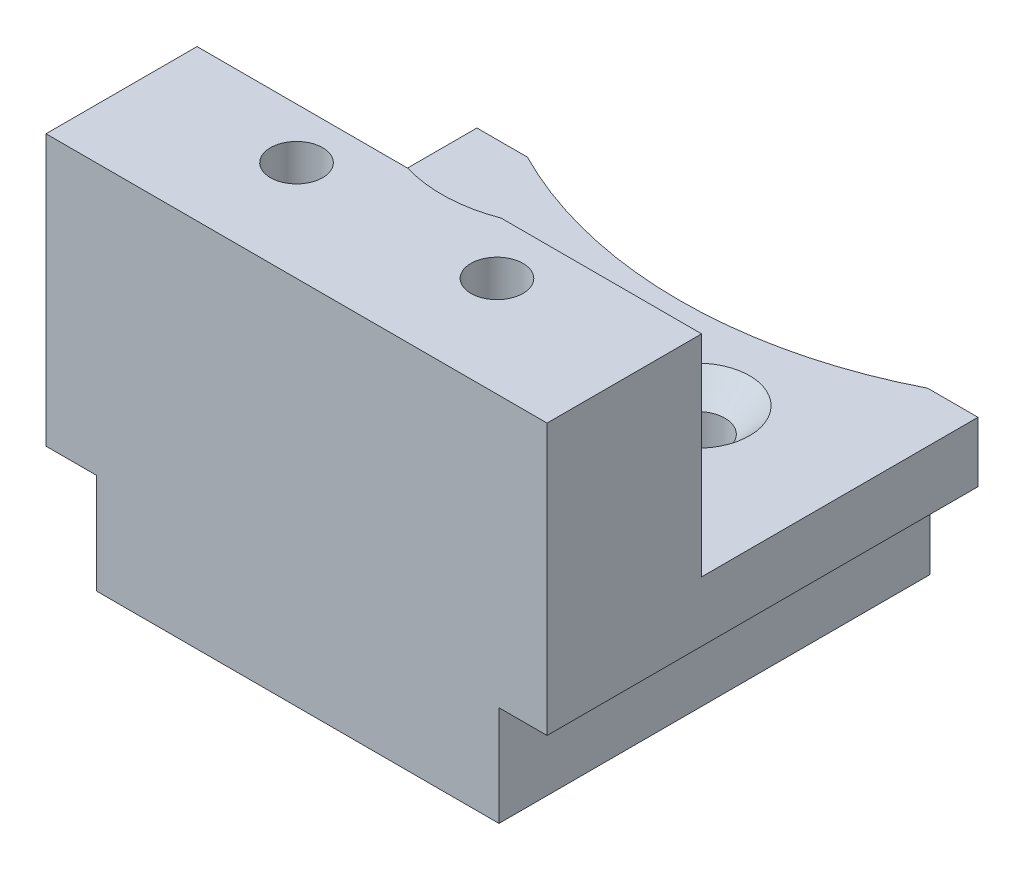
SolidWorks part; units mm, degrees
ref_plane "Front Plane" through (0, 0, 0) normal (0, 0, 1) x (1, 0, 0)
ref_plane "Top Plane" through (0, 0, 0) normal (0, 1, 0) x (1, 0, 0)
ref_plane "Right Plane" through (0, 0, 0) normal (1, 0, 0) x (0, 0, -1)
sketch "Sketch1" plane through (0, 0, 0) normal (0, 1, 0) x (1, 0, 0)
  line L0 (15, 0) -> (15, -46) construction
  line L1 (0, 0) -> (50, 0) construction
  line L2 (0, 0) -> (0, -46)
  line L3 (0, -46) -> (50, -46)
  line L4 (50, 0) -> (50, -46)
  line L5 (35, 0) -> (35, -46) construction
  line L6 (15, -16) -> (35, -16) construction
  line L7 (15, -36) -> (35, -36) construction
  line L8 (0, -3) -> (5.0312, -3)
  line L9 (44.9688, -3) -> (50, -3)
  circle A0 centre (15, -16) radius 2.6
  circle A1 centre (35, -16) radius 2.6
  circle A2 centre (35, -36) radius 2.6
  circle A3 centre (15, -36) radius 2.6
  arc A4 (5.0312, -3) -> (44.9688, -3) centre (25, 36.2077) ccw
  dimension "D5" = 5.2
  dimension "D6" = 5.2
  dimension "D7" = 5.2
  dimension "D8" = 5.2
  dimension "D11" = 44
  dimension "D1" = 15
  dimension "D2" = 15
  dimension "D3" = 10
  dimension "D4" = 20
  dimension "D9" = 50
  dimension "D10" = 46
  dimension "D12" = 3
extrude "Boss-Extrude1" add sketch "Sketch1" along normal blind 6 contours A4 L2 L3 L4 A3 A2 A1 A0
sketch "Sketch2" plane through (0, 6, 0) normal (0, 1, 0) x (1, 0, 0)
  line L1 (0, -46) -> (50, -46) construction
  circle A0 centre (25, -17.5) radius 3.25
  circle A2 centre (15, -16) radius 2.6 construction
  point P10 (25, -46)
  dimension "D1" = 6.5
  dimension "D2" = 1.5
extrude "Boss-Extrude2" add sketch "Sketch2" along normal blind 2
sketch "Sketch3" plane through (0, 8, 0) normal (0, 1, 0) x (1, 0, 0)
  circle A1 centre (25, -17.5) radius 2.5
  dimension "D1" = 5
extrude "Boss-Extrude3" add sketch "Sketch3" along normal blind 2.7
hole_wizard "CSK for M5 Flat Head Machine Screw1" positions "Sketch5" profile "Sketch6" countersink size "M5" standard "ANSI Metric" end condition through all
sketch "Sketch5" plane through (0, 6, 0) normal (0, 1, 0) x (1, 0, 0)
  point P0 (15, -16)
  point P3 (35, -16)
sketch "Sketch6" plane through (15, 6, 16) normal (1, 0, 0) x (0, 0, 1)
  line L0 (0, 0) -> (0, 6)
  line L1 (0, 6) -> (2.75, 6)
  line L2 (2.75, 6) -> (2.75, 2.45)
  line L3 (2.75, 2.45) -> (5.2, 0)
  line L5 (5.2, 0) -> (0, 0)
  line L6 (-2.75, 2.45) -> (-5.2, 0) construction
  line L11 (0, -6.35) -> (0, 107.95) construction
  dimension "Thru Hole Dia." = 5.5
  dimension "Thru Hole Depth" = 6
  dimension "Near C'Sink Dia." = 10.4
  dimension "Near C'Sink Angle" = 90
sketch "Sketch7" plane through (0, 6, 0) normal (0, 1, 0) x (1, 0, 0)
  line L0 (21.0399, -30.9283) -> (0, -30.9283)
  line L3 (0, -3) -> (0, -46) construction
  line L21 (0, -30.9283) -> (0, -46)
  line L22 (0, -46) -> (50, -46)
  line L23 (50, -46) -> (50, -30.5809)
  line L24 (50, -3) -> (50, -46) construction
  line L25 (50, -30.5809) -> (29.9891, -30.5809)
  arc A0 (21.0399, -30.9283) -> (29.9891, -30.5809) centre (25, -17.5) ccw
  circle A1 centre (15, -36) radius 5.5 construction
  circle A2 centre (15, -36) radius 2.6
  circle A3 centre (35, -36) radius 2.6
  dimension "D1" = 28
  dimension "D2" = 11
extrude "Boss-Extrude5" add sketch "Sketch7" along normal blind 21
sketch "Sketch8" plane through (0, 0, 0) normal (-1, 0, 0) x (0, 0, 1)
  line L0 (46, 0) -> (46, -10)
  line L1 (46, -10) -> (3, -10)
  line L2 (3, 0) -> (3, -10)
  line L3 (3, 0) -> (46, 0)
extrude "Boss-Extrude6" add sketch "Sketch8" against normal blind 50
sketch "Sketch9" plane through (0, 0, 3) normal (0, 0, -1) x (-1, 0, 0)
  line L0 (-50, 0) -> (-45.2, 0)
  line L1 (-50, 6) -> (-50, -10) construction
  line L2 (-45.2, 0) -> (-45.2, -10)
  line L3 (-50, -10) -> (0, -10) construction
  line L4 (-45.2, -10) -> (-50, -10)
  line L5 (-50, -10) -> (-50, 0)
  line L6 (-25.5145, 27) -> (-25.5145, -10) construction
  line L7 (-21.0399, 27) -> (-29.9891, 27) construction
  line L12 (0, 0) -> (-5.0312, 0)
  line L13 (-5.0312, 0) -> (-5.0312, -10)
  line L14 (-5.0312, -10) -> (0, -10)
  line L15 (0, -10) -> (0, 0)
extrude "Cut-Extrude1" cut sketch "Sketch9" against normal blind 50
